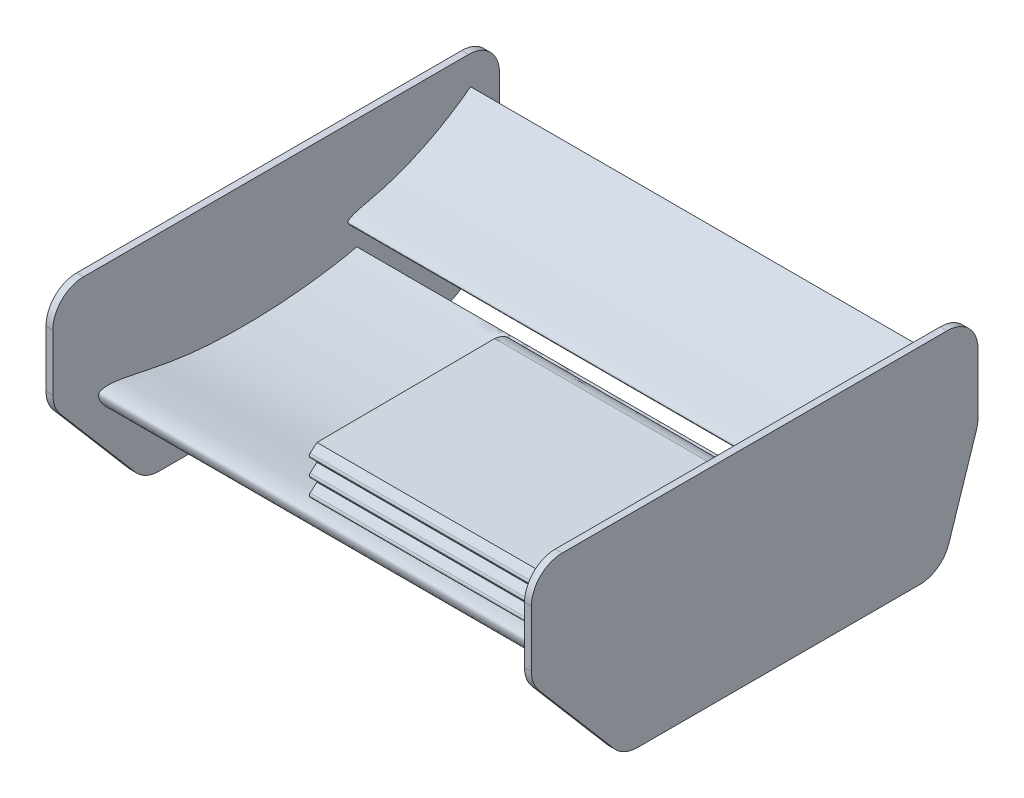
SolidWorks part; units mm, degrees
ref_plane "Front Plane" through (0, 0, 0) normal (0, 0, 1) x (1, 0, 0)
ref_plane "Top Plane" through (0, 0, 0) normal (0, 1, 0) x (1, 0, 0)
ref_plane "Right Plane" through (0, 0, 0) normal (1, 0, 0) x (0, 0, -1)
ref_plane "Soft Top Limit" through (0, 1174.6, 0) normal (0, 1, 0) x (1, 0, 0)
ref_plane "Soft Rear Limit" through (0, 0, -1192.975) normal (0, 0, 1) x (1, 0, 0)
ref_plane "Soft Right Limit" through (-501.65, 0, 0) normal (1, 0, 0) x (0, 0, -1)
ref_plane "Soft Left Limit" through (501.65, 0, 0) normal (1, 0, 0) x (0, 0, -1)
ref_plane "Soft Front Limit" through (0, 0, -165.1) normal (0, 0, 1) x (1, 0, 0)
ref_plane "Slant Limit" through (0, 528.6251, -619.2711) normal (0, -0.6492, 0.7606) x (1, 0, 0)
ref_plane "Bottom" through (0, 476.25, 0) normal (0, 1, 0) x (1, 0, 0)
ref_plane "Midplane" through (0, 0, 0) normal (1, 0, 0) x (0, 0, -1)
curve "Imported Airfoil Curve"
  spline degree 3 poles (0, 2520.0207, 6.126) (0, 2544.889, -1.81) (0, 2521.8965, 7.8839) (0, 2505.3253, 17.7145) (0, 2467.7144, 38.5723) (0, 2424.2142, 62.3813) (0, 2368.0949, 87.8078) (0, 2301.3729, 113.3478) (0, 2223.8362, 140.5377) (0, 2136.6129, 169.2441) (0, 2040.932, 199.097) (0, 1938.2341, 229.6055) (0, 1829.9414, 260.0781) (0, 1717.5266, 289.8586) (0, 1602.4273, 318.1375) (0, 1486.0259, 343.9752) (0, 1369.6902, 366.5754) (0, 1254.3666, 384.7865) (0, 1140.5393, 397.0034) (0, 1028.6357, 403.0127) (0, 919.0585, 402.9406) (0, 812.3986, 397.0375) (0, 709.2785, 385.5985) (0, 610.4299, 369.039) (0, 516.5862, 348.1086) (0, 428.5874, 323.3415) (0, 347.2653, 295.2055) (0, 273.332, 264.2656) (0, 207.4209, 231.0894) (0, 150.0337, 196.3024) (0, 101.596, 160.572) (0, 62.3674, 124.65) (0, 32.4977, 89.3959) (0, 12.0597, 55.6746) (0, 1.683, 26.6201) (0, -0.5567, 6.5526) (0, 0.5894, -3.9947) (0, 1.6947, -9.1451) (0, 2.8711, -12.4915) (0, 3.9449, -14.9776) (0, 4.8993, -16.669) (0, 5.9763, -18.2433) (0, 7.3264, -19.6365) (0, 8.8595, -20.9434) (0, 11.1868, -22.7306) (0, 14.6073, -24.7406) (0, 20.085, -27.4067) (0, 26.8353, -29.9257) (0, 44.6446, -35.1819) (0, 77.8093, -38.8998) (0, 130.2841, -38.2927) (0, 196.3018, -31.4611) (0, 276.2192, -18.4434) (0, 370.8288, 0.8611) (0, 480.7331, 24.811) (0, 605.9792, 50.0099) (0, 745.0759, 74.1542) (0, 895.4497, 95.0846) (0, 1053.6786, 110.004) (0, 1215.6439, 118.3392) (0, 1377.6893, 121.6348) (0, 1537.1174, 120.5125) (0, 1691.5141, 115.2051) (0, 1838.3121, 105.7388) (0, 1975.028, 93.0069) (0, 2099.5942, 78.4581) (0, 2210.5746, 63.1262) (0, 2306.3634, 48.0168) (0, 2387.2069, 33.7158) (0, 2449.0745, 22.0129) (0, 2499.1865, 10.4993) (0, 2520.0207, 6.126) (0, 2544.889, -1.81) (0, 2521.8965, 7.8839) knots -0.016237 -0.007308 -0.001841 0 0.001813 0.006911 0.014576 0.024172 0.035572 0.049013 0.064513 0.081849 0.100772 0.120997 0.142228 0.164173 0.186537 0.209023 0.231367 0.25332 0.274804 0.295858 0.316449 0.336531 0.356033 0.374893 0.39299 0.410197 0.426388 0.441459 0.455334 0.467938 0.479236 0.489204 0.497851 0.505194 0.511308 0.515097 0.516441 0.517273 0.51806 0.518436 0.518797 0.519154 0.519508 0.519887 0.520289 0.52116 0.522116 0.52372 0.525214 0.532575 0.542381 0.554776 0.569931 0.588005 0.609188 0.633329 0.660001 0.688743 0.718873 0.749543 0.780127 0.810209 0.839387 0.867183 0.893104 0.91676 0.937874 0.956199 0.971544 0.983763 0.992692 0.998159 1 1.001813 1.006911 1.014576 periodic
sketch "Airfoils Sketch" plane through (0, 0, 0) normal (1, 0, 0) x (0, 0, -1)
  line L0 (165.1, 1174.6) -> (165.1, 1060.6753) construction
  line L1 (165.1, 1060.6753) -> (663.9798, 476.25) construction
  line L2 (663.9798, 476.25) -> (1192.975, 476.25) construction
  line L3 (1192.975, 476.25) -> (1192.975, 1174.6) construction
  line L4 (1192.975, 1174.6) -> (165.1, 1174.6) construction
  line L5 (509.9361, 1174.6) -> (-509.9361, 1174.6) construction
  line L6 (165.1, 67.0076) -> (165.1, -67.0076) construction
  line L7 (364.7288, 826.8151) -> (873.8134, 230.4351) construction
  line L8 (279.3831, 476.25) -> (-279.3831, 476.25) construction
  line L9 (1192.975, 353.2696) -> (1192.975, -353.2696) construction
  line L10 (364.5896, 868.5327) -> (364.5896, 946) construction
  line L11 (897.9896, 878.5574) -> (897.9896, 1013.4426) construction
  line L12 (897.9896, 946) -> (364.5896, 946) construction
  line L13 (262.9896, 946) -> (1192.975, 946) construction
  line L14 (855.8887, 1048.5614) -> (904.1623, 945.0386) construction
  line L15 (1108.8736, 1167.1505) -> (1157.6222, 1062.6086) construction
  line L16 (1133.2479, 1114.8795) -> (880.0255, 996.8) construction
  line L17 (328.3482, 1114.8795) -> (695.6322, 1114.8795) construction
  line L20 (328.3462, 1124.3171) -> (695.6302, 1126.6315)
  line L21 (603.5565, 1103.1909) -> (695.6302, 1103.7711)
  line L30 (856.3371, 1047.6) -> (1192.975, 1047.6) construction
  line L31 (328.3482, 1079.3195) -> (670.2322, 1079.3195) construction
  line L32 (328.3472, 1088.7564) -> (670.2312, 1090.9108)
  line L33 (603.5252, 1067.63) -> (670.2312, 1068.0503)
  line L34 (328.3482, 1043.7595) -> (644.8322, 1043.7595) construction
  line L35 (328.3482, 1053.1957) -> (644.8322, 1055.19)
  line L36 (603.4939, 1032.0691) -> (644.8322, 1032.3295)
  line L37 (328.3462, 1124.3171) -> (314.1587, 1112.1235)
  line L38 (317.4699, 1103.1909) -> (603.5565, 1103.1909)
  line L39 (328.3472, 1088.7564) -> (314.1595, 1076.5625)
  line L40 (317.4707, 1067.63) -> (603.5252, 1067.63)
  line L41 (328.3482, 1053.1957) -> (314.1603, 1041.0016)
  line L42 (317.4715, 1032.0691) -> (603.4939, 1032.0691)
  arc A0 (730.3858, 1100.5822) -> (723.0285, 1095.3489) centre (725.3568, 1099.864) cw
  arc A1 (700.7756, 1066.573) -> (693.0652, 1061.4974) centre (695.7535, 1065.8077) cw
  arc A2 (675.6555, 1030.8779) -> (668.1478, 1025.6011) centre (670.6479, 1030.0233) cw
  arc A3 (314.1603, 1041.0016) -> (317.4715, 1032.0691) centre (317.4715, 1037.1491) ccw
  arc A4 (314.1595, 1076.5625) -> (317.4707, 1067.63) centre (317.4707, 1072.71) ccw
  arc A5 (314.1587, 1112.1235) -> (317.4699, 1103.1909) centre (317.4699, 1108.2709) ccw
  spline S0 degree 3 poles (893.7912, 944.7229) (899.0172, 946.3778) (894.1843, 944.3529) (890.6998, 942.2962) (882.7919, 937.9336) (873.6459, 932.9541) (861.8492, 927.6408) (847.826, 922.3086) (831.5308, 916.6349) (813.2009, 910.6474) (793.0943, 904.4229) (771.5139, 898.0641) (748.7586, 891.7155) (725.138, 885.5141) (700.9544, 879.6292) (676.4985, 874.2577) (652.0578, 869.5659) (627.8318, 865.7954) (603.9228, 863.283) (580.4206, 862.0732) (557.4098, 862.1394) (535.0144, 863.4287) (513.3649, 865.8789) (492.6147, 869.4025) (472.9176, 873.8415) (454.4497, 879.0835) (437.3855, 885.0299) (421.8742, 891.5616) (408.0485, 898.5592) (396.0136, 905.8911) (385.8586, 913.417) (377.6374, 920.9787) (371.3813, 928.3959) (367.1052, 935.4868) (364.9396, 941.5929) (364.4786, 945.8081) (364.7242, 948.0225) (364.9587, 949.1035) (365.2073, 949.8057) (365.434, 950.3273) (365.6352, 950.682) (365.8621, 951.0121) (366.1463, 951.304) (366.4688, 951.5778) (366.9584, 951.952) (367.6776, 952.3725) (368.8291, 952.9298) (370.2479, 953.4556) (373.9902, 954.5511) (380.9564, 955.3164) (391.9757, 955.1645) (405.8359, 953.6991) (422.6123, 950.9282) (442.4709, 946.8302) (465.5393, 941.7496) (491.8288, 936.3995) (521.0273, 931.2645) (552.5956, 926.7991) (585.8161, 923.5923) (619.8244, 921.7664) (653.8518, 920.9989) (687.3317, 921.1602) (719.7569, 922.2028) (750.5884, 924.1223) (779.3042, 926.7322) (805.4694, 929.7293) (828.782, 932.8973) (848.9044, 936.0255) (865.8879, 938.991) (878.8853, 941.4197) (889.4141, 943.8142) (893.7912, 944.7229) (899.0172, 946.3778) (894.1843, 944.3529) knots -0.016237 -0.007308 -0.001841 0 0.001813 0.006911 0.014576 0.024172 0.035572 0.049013 0.064513 0.081849 0.100772 0.120997 0.142228 0.164173 0.186537 0.209023 0.231367 0.25332 0.274804 0.295858 0.316449 0.336531 0.356033 0.374893 0.39299 0.410197 0.426388 0.441459 0.455334 0.467938 0.479236 0.489204 0.497851 0.505194 0.511308 0.515097 0.516441 0.517273 0.51806 0.518436 0.518797 0.519154 0.519508 0.519887 0.520289 0.52116 0.522116 0.52372 0.525214 0.532575 0.542381 0.554776 0.569931 0.588005 0.609188 0.633329 0.660001 0.688743 0.718873 0.749543 0.780127 0.810209 0.839387 0.867183 0.893104 0.91676 0.937874 0.956199 0.971544 0.983763 0.992692 0.998159 1 1.001813 1.006911 1.014576 only from (897.9896, 946) to (897.9896, 946)
  spline S1 degree 3 poles (1131.5375, 1113.3438) (1133.6521, 1115.2864) (1131.806, 1113.2552) (1130.6071, 1111.5075) (1127.8187, 1107.6858) (1124.5791, 1103.2972) (1120.1551, 1098.1634) (1114.6782, 1092.5276) (1108.1983, 1086.2269) (1100.822, 1079.3267) (1092.6546, 1071.9207) (1083.8174, 1064.1247) (1074.4201, 1056.0734) (1064.5795, 1047.9005) (1054.4014, 1039.7532) (1043.9805, 1031.7893) (1033.4164, 1024.1515) (1022.7502, 1016.9986) (1011.956, 1010.5131) (1001.0665, 1004.736) (990.1279, 999.6735) (979.2106, 995.3279) (968.3905, 991.6985) (957.7597, 988.7777) (947.4262, 986.5247) (937.4984, 984.925) (928.0811, 983.9704) (919.2715, 983.6375) (911.1589, 983.8989) (903.8225, 984.7154) (897.3355, 986.0401) (891.7587, 987.81) (887.1468, 989.9462) (883.547, 992.3659) (881.1672, 994.7853) (880.0153, 996.6843) (879.6417, 997.7899) (879.5137, 998.355) (879.4763, 998.7434) (879.4684, 999.0412) (879.4854, 999.2542) (879.52, 999.4611) (879.5903, 999.6626) (879.6829, 999.864) (879.8324, 1000.15) (880.0808, 1000.5088) (880.5041, 1001.0283) (881.0612, 1001.592) (882.5953, 1002.9405) (885.733, 1004.8459) (890.9978, 1007.2132) (897.9021, 1009.5858) (906.4798, 1011.9841) (916.8145, 1014.4348) (928.8905, 1017.1296) (942.5554, 1020.4095) (957.5536, 1024.4354) (973.5286, 1029.3038) (990.0094, 1035.1356) (1006.5584, 1041.7972) (1022.8822, 1048.9655) (1038.7405, 1056.4536) (1053.903, 1064.1266) (1068.1148, 1071.863) (1081.1694, 1079.4589) (1092.9274, 1086.674) (1103.2934, 1093.3387) (1112.1536, 1099.2783) (1119.5597, 1104.4457) (1125.1924, 1108.476) (1129.6607, 1111.9435) (1131.5375, 1113.3438) (1133.6521, 1115.2864) (1131.806, 1113.2552) knots -0.016237 -0.007308 -0.001841 0 0.001813 0.006911 0.014576 0.024172 0.035572 0.049013 0.064513 0.081849 0.100772 0.120997 0.142228 0.164173 0.186537 0.209023 0.231367 0.25332 0.274804 0.295858 0.316449 0.336531 0.356033 0.374893 0.39299 0.410197 0.426388 0.441459 0.455334 0.467938 0.479236 0.489204 0.497851 0.505194 0.511308 0.515097 0.516441 0.517273 0.51806 0.518436 0.518797 0.519154 0.519508 0.519887 0.520289 0.52116 0.522116 0.52372 0.525214 0.532575 0.542381 0.554776 0.569931 0.588005 0.609188 0.633329 0.660001 0.688743 0.718873 0.749543 0.780127 0.810209 0.839387 0.867183 0.893104 0.91676 0.937874 0.956199 0.971544 0.983763 0.992692 0.998159 1 1.001813 1.006911 1.014576 only from (1133.2479, 1114.8795) to (1133.2479, 1114.8795)
  spline S2 degree 3 poles (695.6302, 1126.6315) (710.2979, 1124.7452) (728.0044, 1117.2552) (730.3858, 1100.5822) knots 0 0 0 0 0.846942 0.846942 0.846942 0.846942
  spline S3 degree 3 poles (670.2312, 1090.9108) (687.1645, 1091.5322) (698.5585, 1081.121) (700.7756, 1066.573) knots 0 0 0 0 0.809071 0.809071 0.809071 0.809071
  spline S4 degree 3 poles (644.8322, 1055.19) (661.4632, 1055.4518) (673.1617, 1045.4901) (675.6555, 1030.8779) knots 0 0 0 0 0.816938 0.816938 0.816938 0.816938
  spline S5 degree 3 poles (695.6302, 1103.7711) (707.5509, 1101.184) (713.9456, 1100.0327) (723.0285, 1095.3489) knots 0 0 0 0 0.77437 0.77437 0.77437 0.77437
  spline S6 degree 3 poles (670.2312, 1068.0503) (678.2263, 1068.0172) (686.3172, 1065.7061) (693.0652, 1061.4974) knots 0 0 0 0 0.706874 0.706874 0.706874 0.706874
  spline S7 degree 3 poles (644.8322, 1032.3295) (653.0102, 1031.962) (661.0773, 1029.5984) (668.1478, 1025.6011) knots 0 0 0 0 0.717847 0.717847 0.717847 0.717847
  point P31 (511.2249, 1140.1248)
  point P32 (511.9902, 1114.8795)
  point P36 (511.2249, 1097.6814)
  point P38 (499.2902, 1079.3195)
  point P45 (486.0425, 1060.6753)
  point P47 (486.5902, 1043.7595)
  point P52 (473.5242, 1043.7595)
  point P60 (0, 0)
  point P80 (723.0285, 1114.8795)
  point P81 (695.7535, 1079.3195)
  point P82 (0, 0)
  point P83 (698.1901, 1104.0324)
  dimension "D15" = 5.08
  dimension "D16" = 5.08
  dimension "D17" = 5.08
  dimension "D18" = 5.08
  dimension "D19" = 5.08
  dimension "D20" = 5.08
  dimension "D1" = 533.4
  dimension "D2" = 228.6
  dimension "D3" = 0
  dimension "D4" = 101.6
  dimension "D5" = 279.4
  dimension "D6" = 59.7205
  dimension "D7" = 367.284
  dimension "D8" = 341.884
  dimension "D9" = 316.484
  dimension "D10" = 12.7
  dimension "D11" = 12.7
  dimension "D12" = 22.86
  dimension "D13" = 22.86
  dimension "D14" = 22.86
extrude "Extruded Airfoils" add sketch "Airfoils Sketch" along normal offset from surface (487.45 mm away) 14.2 up to plane "Soft Left Limit"
sketch "Endplate Sketch" plane through (501.65, 0, 0) normal (1, 0, 0) x (0, 0, -1)
  line L6 (333.4477, 1174.6) -> (1129.475, 1174.6)
  line L7 (1192.975, 1174.6) -> (165.1, 1174.6) construction
  line L8 (1192.975, 1111.1) -> (1192.975, 986.6717)
  line L9 (1192.975, 476.25) -> (1192.975, 1174.6) construction
  line L11 (1189.8464, 966.9854) -> (1132.8969, 792.34)
  line L12 (1072.5255, 748.5263) -> (489.1772, 748.5263)
  line L19 (440.8805, 770.7991) -> (285.151, 953.2323)
  line L26 (269.9477, 994.4595) -> (269.9477, 1111.1)
  line L28 (165.1, 1060.6753) -> (663.9798, 476.25) construction
  arc A12 (1129.475, 1174.6) -> (1192.975, 1111.1) centre (1129.475, 1111.1) cw
  arc A13 (1192.975, 986.6717) -> (1189.8464, 966.9854) centre (1129.475, 986.6717) cw
  arc A14 (1132.8969, 792.34) -> (1072.5255, 748.5263) centre (1072.5255, 812.0263) cw
  arc A15 (489.1772, 748.5263) -> (440.8805, 770.7991) centre (489.1772, 812.0263) cw
  arc A16 (285.151, 953.2323) -> (269.9477, 994.4595) centre (333.4477, 994.4595) cw
  arc A17 (333.4477, 1174.6) -> (269.9477, 1111.1) centre (333.4477, 1111.1) ccw
  point P16 (1192.975, 1174.6)
  point P19 (1192.975, 976.5799)
  point P29 (269.9477, 1174.6)
  dimension "D1" = 63.5
extrude "Extruded Endplate" add sketch "Endplate Sketch" against normal up to surface (14.2 mm away)
mirror "Mirror" about plane through (0, 0, 0) normal (1, 0, 0) of bodies 106
